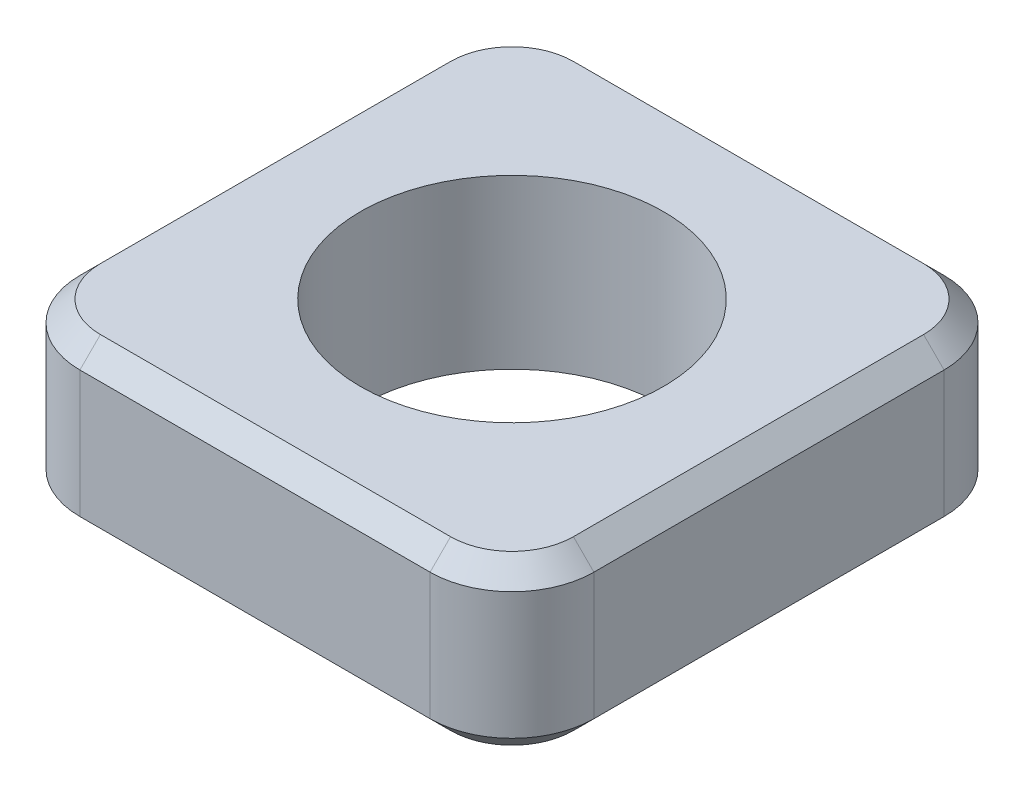
SolidWorks part; units mm, degrees
ref_plane "Front Plane" through (0, 0, 0) normal (0, 0, 1) x (1, 0, 0)
ref_plane "Top Plane" through (0, 0, 0) normal (0, 1, 0) x (1, 0, 0)
ref_plane "Right Plane" through (0, 0, 0) normal (1, 0, 0) x (0, 0, -1)
sketch "Sketch1" plane through (0, 0, 0) normal (0, 1, 0) x (1, 0, 0)
  line L0 (-3.1375, 3.1375) -> (0, 0) construction
  line L1 (-2.1375, 3.1375) -> (2.1375, 3.1375)
  line L2 (-3.1375, 2.1375) -> (-3.1375, -2.1375)
  line L3 (-2.1375, -3.1375) -> (2.1375, -3.1375)
  line L4 (3.1375, 2.1375) -> (3.1375, -2.1375)
  line L5 (0, 0) -> (-3.1375, -3.1375) construction
  line L6 (3.1375, -3.1375) -> (0, 0) construction
  circle A0 centre (0, 0) radius 1.85
  arc A1 (2.1375, -3.1375) -> (3.1375, -2.1375) centre (2.1375, -2.1375) ccw
  arc A2 (2.1375, 3.1375) -> (3.1375, 2.1375) centre (2.1375, 2.1375) cw
  arc A3 (-2.1375, 3.1375) -> (-3.1375, 2.1375) centre (-2.1375, 2.1375) ccw
  arc A4 (-3.1375, -2.1375) -> (-2.1375, -3.1375) centre (-2.1375, -2.1375) ccw
  point P12 (3.1375, 3.1375)
  dimension "D2" = 3.7
  dimension "D3" = 1
  dimension "D1" = 6.275
extrude "Boss-Extrude1" add sketch "Sketch1" along normal blind 2.05
chamfer "Chamfer1" distance 0.25 angle 45 16 edges at (0, 0, -3.1375) (-2.8446, 0, -2.8446) (2.8446, 0, -2.8446) (-3.1375, 0, 0) (3.1375, 0, 0) (-2.8446, 0, 2.8446) (2.8446, 0, 2.8446) (0, 0, 3.1375) (3.1375, 2.05, 0) (2.8446, 2.05, -2.8446) (2.8446, 2.05, 2.8446) (0, 2.05, -3.1375) (0, 2.05, 3.1375) (-2.8446, 2.05, -2.8446) (-2.8446, 2.05, 2.8446) (-3.1375, 2.05, 0)
